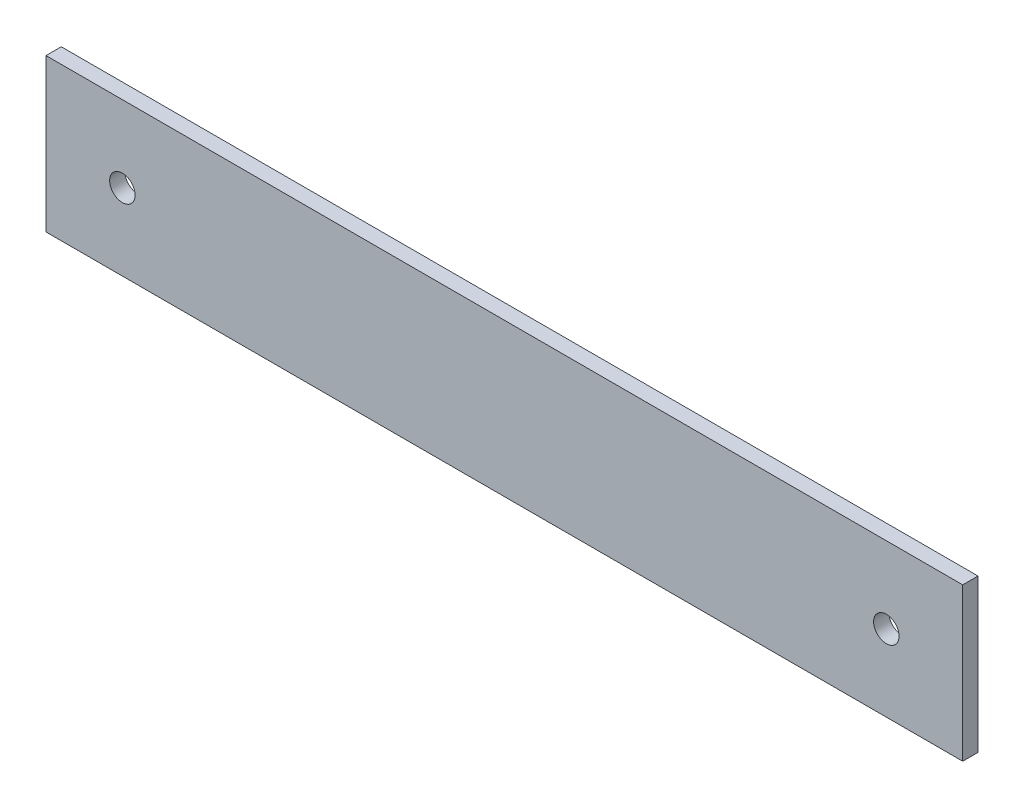
SolidWorks part; units mm, degrees
ref_plane "Front Plane" through (0, 0, 0) normal (0, 0, 1) x (1, 0, 0)
ref_plane "Top Plane" through (0, 0, 0) normal (0, 1, 0) x (1, 0, 0)
ref_plane "Right Plane" through (0, 0, 0) normal (1, 0, 0) x (0, 0, -1)
sketch "Sketch1" plane through (0, 0, 0) normal (0, 0, 1) x (1, 0, 0)
  line L1 (0, 0) -> (180, 0)
  line L2 (0, 0) -> (0, 30)
  line L3 (0, 30) -> (180, 30)
  line L4 (180, 0) -> (180, 30)
  circle A0 centre (15, 15) radius 2.5
  circle A1 centre (165, 15) radius 2.5
  dimension "D3" = 5
  dimension "D4" = 5
  dimension "D1" = 180
  dimension "D2" = 30
  dimension "D5" = 15
  dimension "D6" = 15
  dimension "D7" = 150
  dimension "D8" = 15
extrude "Boss-Extrude1" add sketch "Sketch1" along normal blind 3
